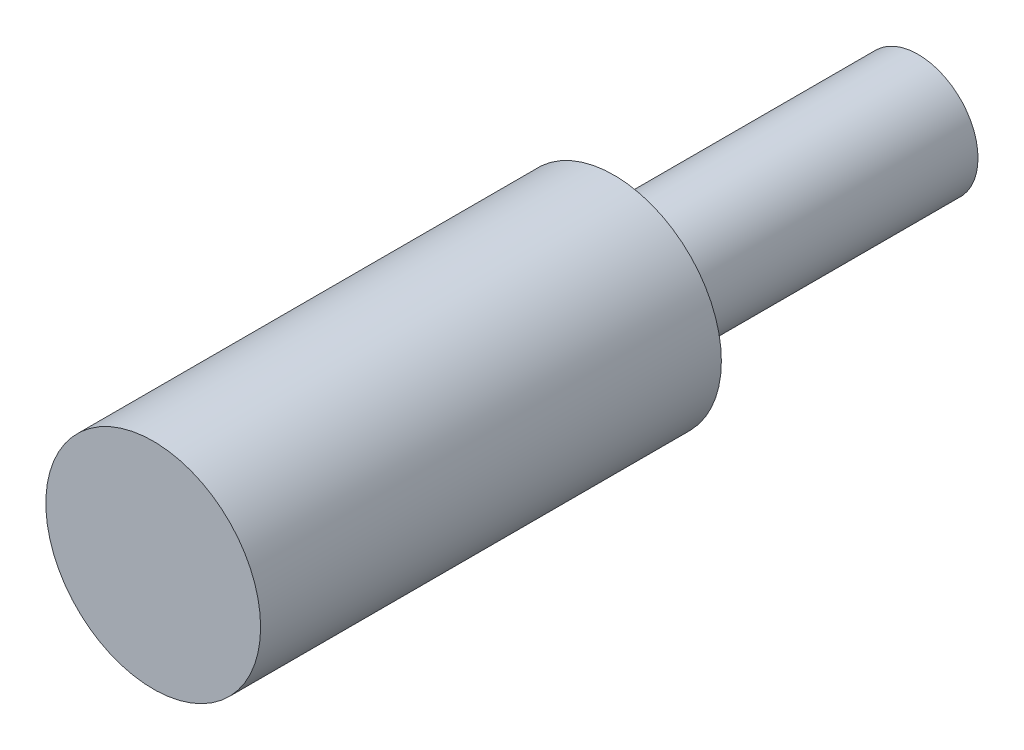
SolidWorks part; units mm, degrees
ref_plane "Plan de face" through (0, 0, 0) normal (0, 0, 1) x (1, 0, 0)
ref_plane "Plan de dessus" through (0, 0, 0) normal (0, 1, 0) x (1, 0, 0)
ref_plane "Plan de droite" through (0, 0, 0) normal (1, 0, 0) x (0, 0, -1)
sketch "Esquisse1" plane through (0, 0, 0) normal (0, 0, 1) x (1, 0, 0)
  circle A0 centre (0, 0) radius 6.5
  dimension "D1" = 13
extrude "Boss.-Extru.1" add sketch "Esquisse1" along normal blind 33
sketch "Esquisse2" plane through (0, 0, 33) normal (0, 0, 1) x (1, 0, 0)
  circle A0 centre (0, 0) radius 11.6527
extrude "Boss.-Extru.2" add sketch "Esquisse2" along normal blind 50
